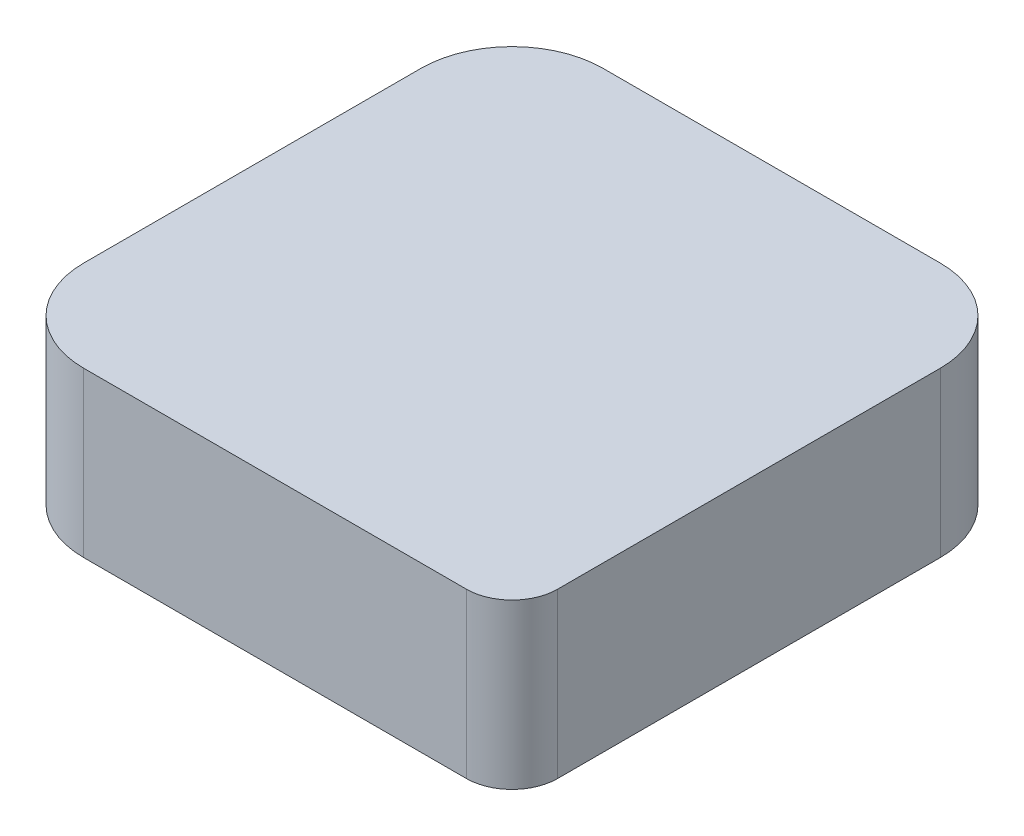
SolidWorks part; units mm, degrees
ref_plane "Front Plane" through (0, 0, 0) normal (0, 0, 1) x (1, 0, 0)
ref_plane "Top Plane" through (0, 0, 0) normal (0, 1, 0) x (1, 0, 0)
ref_plane "Right Plane" through (0, 0, 0) normal (1, 0, 0) x (0, 0, -1)
sketch "Sketch1" plane through (0, 0, 0) normal (0, 1, 0) x (1, 0, 0)
  line L1 (0, 0) -> (57, 0)
  line L2 (0, 0) -> (0, 57)
  line L3 (0, 57) -> (57, 57)
  line L4 (57, 0) -> (57, 57)
  dimension "D1" = 57
  dimension "D2" = 57
extrude "Boss-Extrude1" add sketch "Sketch1" along normal blind 18
fillet "Fillet1" radius 5 1 edges at (57, 9, 0)
fillet "Fillet2" radius 10 3 edges at (0, 9, 0) (0, 9, -57) (57, 9, -57)
